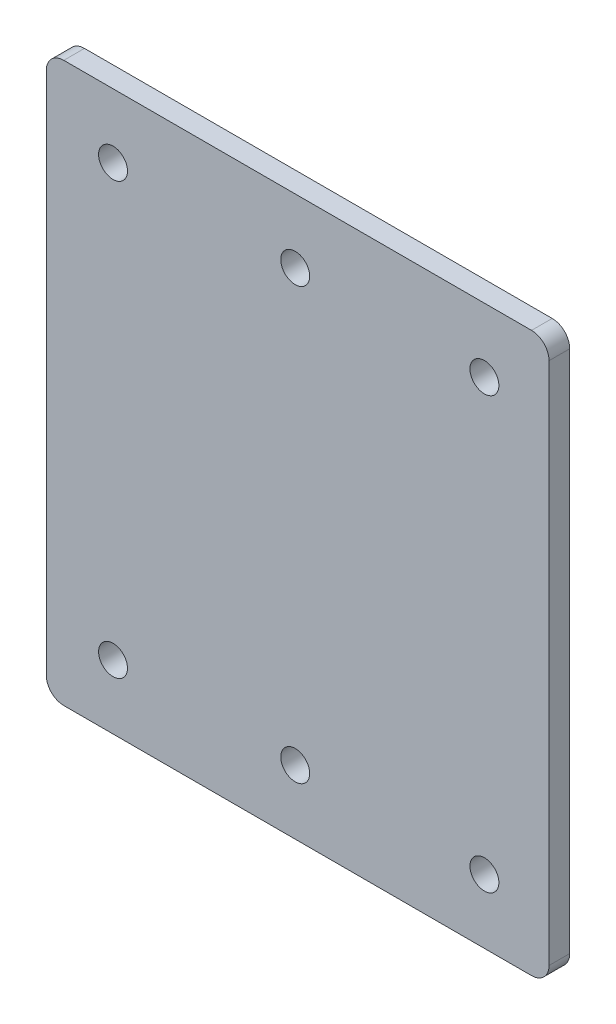
SolidWorks part; units mm, degrees
material "Acrylic (Medium-high impact)"
ref_plane "X-Y Datum" through (0, 0, 0) normal (0, 0, 1) x (1, 0, 0)
ref_plane "X-Z Datum" through (0, 0, 0) normal (0, 1, 0) x (1, 0, 0)
ref_plane "Y-Z Datum" through (0, 0, 0) normal (1, 0, 0) x (0, 0, -1)
sketch "Sketch2" plane through (0, 0, 0) normal (0, 0, 1) x (1, 0, 0)
  line L0 (0, 40.513) -> (0, -40.513) construction
  line L1 (-36.449, 40.513) -> (36.449, 40.513) construction
  line L2 (-36.449, 40.513) -> (-36.449, -40.513) construction
  line L3 (-36.449, -40.513) -> (36.449, -40.513) construction
  line L4 (36.449, 40.513) -> (36.449, -40.513) construction
  line L5 (-36.449, 40.513) -> (36.449, -40.513) construction
  line L6 (-36.449, -40.513) -> (36.449, 40.513) construction
  line L7 (-36.449, 0) -> (36.449, 0) construction
  line L8 (-36.449, -37.973) -> (-36.449, 37.973)
  line L9 (-33.909, 40.513) -> (33.909, 40.513)
  line L10 (36.449, 37.973) -> (36.449, -37.973)
  line L11 (33.909, -40.513) -> (-33.909, -40.513)
  arc A4 (33.909, -40.513) -> (36.449, -37.973) centre (33.909, -37.973) ccw
  arc A5 (-33.909, -40.513) -> (-36.449, -37.973) centre (-33.909, -37.973) cw
  arc A6 (36.449, 37.973) -> (33.909, 40.513) centre (33.909, 37.973) ccw
  arc A7 (-33.909, 40.513) -> (-36.449, 37.973) centre (-33.909, 37.973) ccw
  point P0 (0, 0)
  point P6 (-34.005, 38.0253)
  point P7 (-33.005, 38.07)
  point P13 (-33.9531, 38.07)
  point P16 (36.449, -40.513)
  point P21 (-36.449, -40.513)
  point P24 (36.449, 40.513)
  dimension "D3" = 2.54
  dimension "D1" = 72.898
  dimension "D2" = 81.026
extrude "Boss-Extrude1" add sketch "Sketch2" against normal blind 2.9972
sketch "Sketch3" plane through (0, 0, 0) normal (0, 0, 1) x (1, 0, 0)
  line L0 (33.909, 40.513) -> (-33.909, 40.513) construction
  line L1 (-36.449, 37.973) -> (-36.449, -37.973) construction
  line L2 (36.449, -37.973) -> (36.449, 37.973) construction
  line L3 (55.1739, 0) -> (-55.1739, 0) construction
  circle A0 centre (-26.7716, 31.2166) radius 2.0955
  circle A1 centre (-0.3556, 31.2166) radius 2.0955
  circle A2 centre (27.0764, 31.2166) radius 2.0955
  circle A3 centre (27.0764, -31.2166) radius 2.0955
  circle A4 centre (-0.3556, -31.2166) radius 2.0955
  circle A5 centre (-26.7716, -31.2166) radius 2.0955
  dimension "D4" = 4.191
  dimension "D5" = 4.191
  dimension "D6" = 4.191
  dimension "D1" = 9.2964
  dimension "D2" = 9.2964
  dimension "D3" = 9.2964
  dimension "D7" = 9.6774
  dimension "D8" = 36.0934
  dimension "D9" = 9.3726
extrude "Cut-Extrude1" cut sketch "Sketch3" against normal through all
